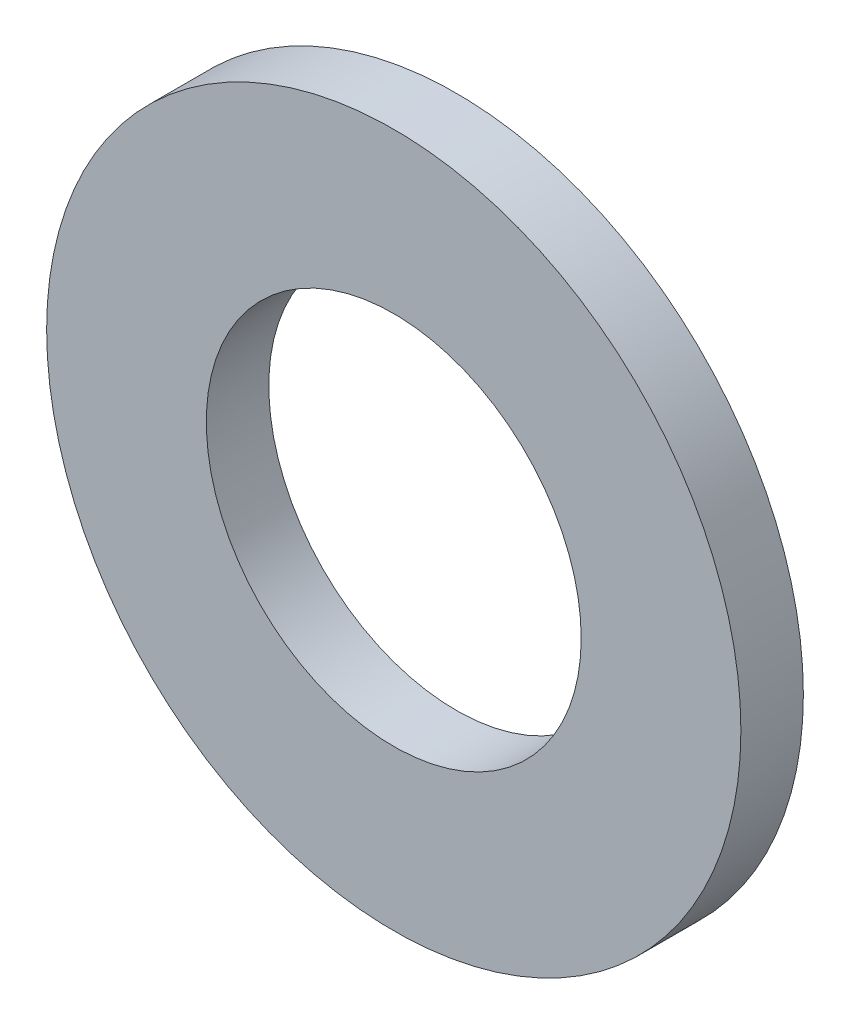
SolidWorks part; units mm, degrees
material "AISI 1020"
ref_plane "Plano frontal" through (0, 0, 0) normal (0, 0, 1) x (1, 0, 0)
ref_plane "Plano superior" through (0, 0, 0) normal (0, 1, 0) x (1, 0, 0)
ref_plane "Plano direito" through (0, 0, 0) normal (1, 0, 0) x (0, 0, -1)
sketch "Esboço1" plane through (0, 0, 0) normal (0, 0, 1) x (1, 0, 0)
  circle A0 centre (0, 0) radius 2.7
  circle A1 centre (0, 0) radius 5
  dimension "D1" = 10
  dimension "D2" = 5.4
extrude "Ressalto-extrusão1" add sketch "Esboço1" along normal blind 0.9
